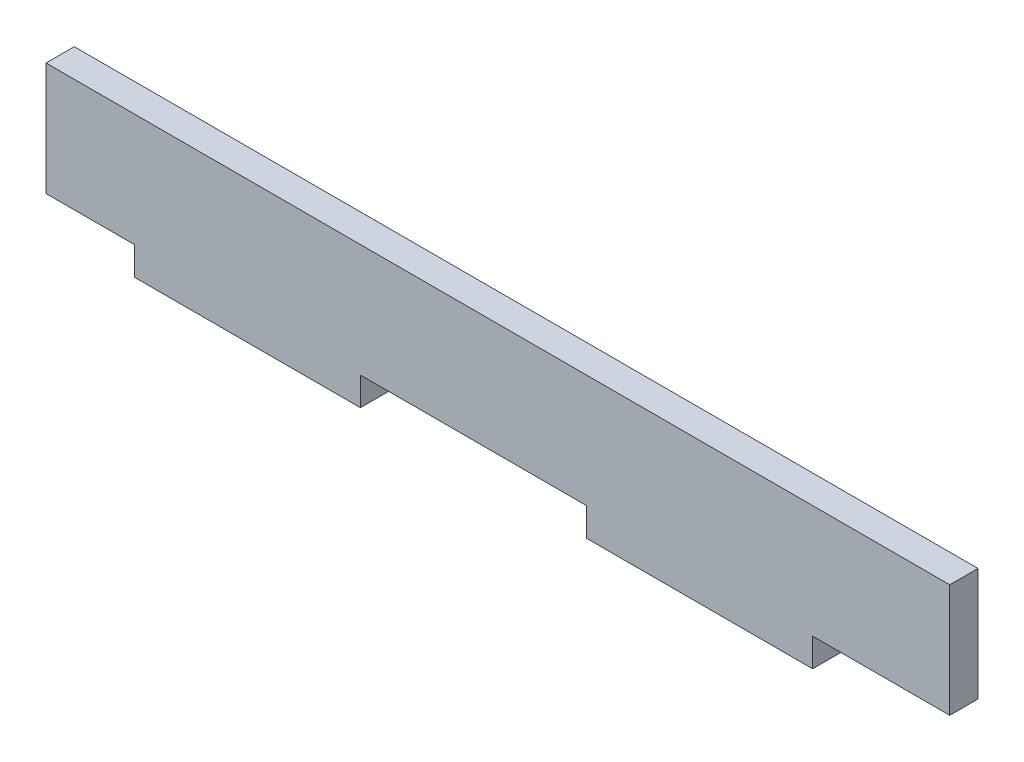
SolidWorks part; units mm, degrees
ref_plane "Front Plane" through (0, 0, 0) normal (0, 0, 1) x (1, 0, 0)
ref_plane "Top Plane" through (0, 0, 0) normal (0, 1, 0) x (1, 0, 0)
ref_plane "Right Plane" through (0, 0, 0) normal (1, 0, 0) x (0, 0, -1)
sketch "Sketch1" plane through (0, 0, 0) normal (0, 0, 1) x (1, 0, 0)
  line L0 (30.9702, 53.6534) -> (30.9702, 26.2534) construction
  line L1 (30.9702, 18.6034) -> (234, 18.6034)
  line L2 (30.9702, 18.6034) -> (30.9702, 50.3534)
  line L3 (30.9702, 50.3534) -> (234, 50.3534)
  line L4 (234, 18.6034) -> (234, 50.3534)
  line L5 (30.9702, 18.6034) -> (234, 50.3534) construction
  line L6 (30.9702, 50.3534) -> (234, 18.6034) construction
  line L7 (234, 50.3534) -> (234, 24.9534) construction
  point P4 (132.4851, 34.4784)
  point P5 (0, 0)
  point P6 (0, 0)
  point P7 (141.905, 0)
  point P8 (252.7131, 0)
  point P9 (40.7359, 50.3534)
  point P14 (0, 0)
  dimension "D1" = 31.75
extrude "Boss-Extrude1" add sketch "Sketch1" along normal blind 6.35
sketch "Sketch2" plane through (0, 0, 6.35) normal (0, 0, 1) x (1, 0, 0)
  line L0 (30.9702, 18.6034) -> (234, 18.6034) construction
  line L1 (30.9702, 18.6034) -> (50.8, 18.6034)
  line L2 (30.9702, 18.6034) -> (30.9702, 24.9534)
  line L3 (30.9702, 24.9534) -> (50.8, 24.9534)
  line L4 (50.8, 18.6034) -> (50.8, 24.9534)
  line L5 (30.9702, 18.6034) -> (50.8, 24.9534) construction
  line L6 (30.9702, 24.9534) -> (50.8, 18.6034) construction
  line L7 (234, 18.6034) -> (234, 50.3534) construction
  line L8 (101.6, 18.6034) -> (152.4, 18.6034)
  line L9 (101.6, 18.6034) -> (101.6, 24.9534)
  line L10 (101.6, 24.9534) -> (152.4, 24.9534)
  line L11 (152.4, 18.6034) -> (152.4, 24.9534)
  line L12 (101.6, 18.6034) -> (152.4, 24.9534) construction
  line L13 (101.6, 24.9534) -> (152.4, 18.6034) construction
  line L14 (203.2, 18.6034) -> (234, 18.6034)
  line L15 (203.2, 18.6034) -> (203.2, 24.9534)
  line L16 (203.2, 24.9534) -> (234, 24.9534)
  line L17 (234, 18.6034) -> (234, 24.9534)
  line L18 (203.2, 18.6034) -> (234, 24.9534) construction
  line L19 (203.2, 24.9534) -> (234, 18.6034) construction
  point P4 (40.8851, 21.7784)
  point P11 (127, 21.7784)
  point P18 (218.6, 21.7784)
  dimension "D1" = 6.35
  dimension "D2" = 50.8
  dimension "D3" = 50.8
  dimension "D4" = 50.8
extrude "Cut-Extrude1" cut sketch "Sketch2" against normal up to next
